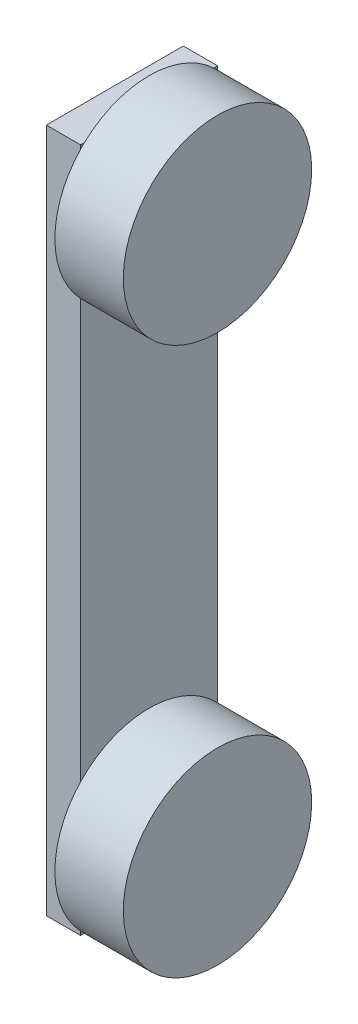
SolidWorks part; units mm, degrees
material "Plain Carbon Steel"
ref_plane "Front Plane" through (0, 0, 0) normal (0, 0, 1) x (1, 0, 0)
ref_plane "Top Plane" through (0, 0, 0) normal (0, 1, 0) x (1, 0, 0)
ref_plane "Right Plane" through (0, 0, 0) normal (1, 0, 0) x (0, 0, -1)
sketch "Sketch1" plane through (0, 0, 0) normal (1, 0, 0) x (0, 0, -1)
  line L1 (-25.4, -127) -> (25.4, -127)
  line L2 (-25.4, -127) -> (-25.4, 127)
  line L3 (-25.4, 127) -> (25.4, 127)
  line L4 (25.4, -127) -> (25.4, 127)
  line L5 (-25.4, -127) -> (25.4, 127) construction
  line L6 (-25.4, 127) -> (25.4, -127) construction
  point P0 (0, 0)
  dimension "D1" = 254
  dimension "D2" = 50.8
extrude "Boss-Extrude1" add sketch "Sketch1" along normal mid plane 12.7
sketch "Sketch2" plane through (6.35, 0, 0) normal (1, 0, 0) x (0, 0, -1)
  line L0 (0, 20.955) -> (0, -20.955) construction
  line L1 (20.955, 0) -> (-20.955, 0) construction
  circle A0 centre (0, 101.6) radius 34.925
  circle A1 centre (0, -101.6) radius 34.925
  dimension "D1" = 69.85
  dimension "D2" = 69.85
  dimension "D3" = 101.6
  dimension "D4" = 101.6
extrude "Boss-Extrude2" add sketch "Sketch2" along normal blind 25.4
